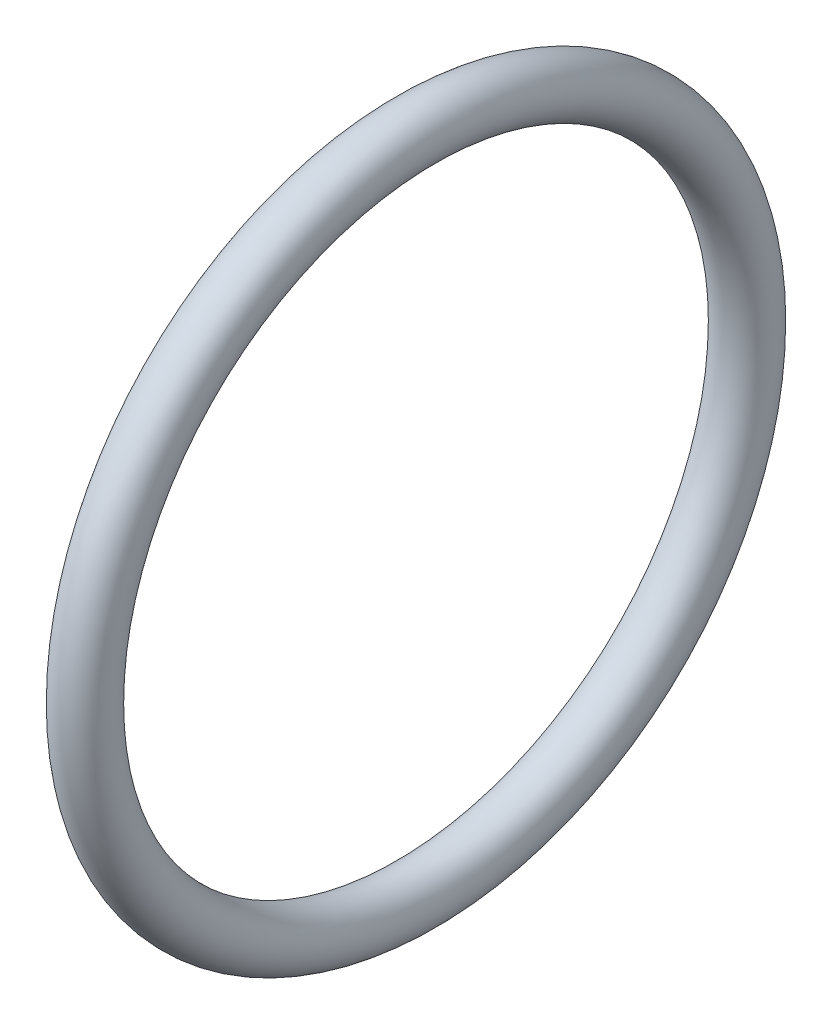
SolidWorks part; units mm, degrees
ref_plane "前视基准面" through (0, 0, 0) normal (0, 0, 1) x (1, 0, 0)
ref_plane "上视基准面" through (0, 0, 0) normal (0, 1, 0) x (1, 0, 0)
ref_plane "右视基准面" through (0, 0, 0) normal (1, 0, 0) x (0, 0, -1)
sketch "草图1" plane through (0, 0, 0) normal (0, 0, 1) x (1, 0, 0)
  line L0 (0, 0) -> (68.602, 0) construction
  circle A0 centre (0, 18.75) radius 1.55
  circle A1 centre (0, -18.75) radius 1.55 construction
revolve "旋转1" add sketch "草图1" angle 360 about L0
